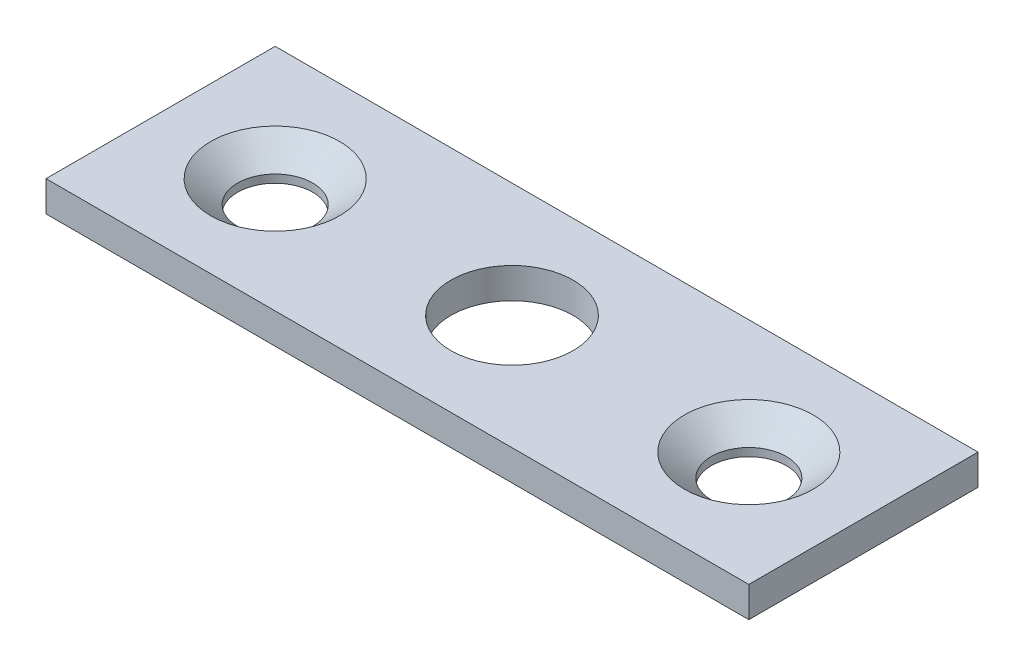
SolidWorks part; units mm, degrees
ref_plane "Front Plane" through (0, 0, 0) normal (0, 0, 1) x (1, 0, 0)
ref_plane "Top Plane" through (0, 0, 0) normal (0, 1, 0) x (1, 0, 0)
ref_plane "Right Plane" through (0, 0, 0) normal (1, 0, 0) x (0, 0, -1)
sketch "Sketch1" plane through (0, 0, 0) normal (0, 1, 0) x (1, 0, 0)
  line L1 (-23, -7.5) -> (23, -7.5)
  line L2 (-23, -7.5) -> (-23, 7.5)
  line L3 (-23, 7.5) -> (23, 7.5)
  line L4 (23, -7.5) -> (23, 7.5)
  line L5 (-23, -7.5) -> (23, 7.5) construction
  line L6 (-23, 7.5) -> (23, -7.5) construction
  circle A0 centre (0, 0) radius 4
  point P0 (0, 0)
  dimension "D2" = 8
  dimension "D1" = 46
  dimension "15" = 15
extrude "Boss-Extrude1" add sketch "Sketch1" along normal blind 2
hole_wizard "CSK for #8 Flat Head Machine Screw (100)1" positions "Sketch4" profile "Sketch5" countersink size "#8" standard "ANSI Inch"
sketch "Sketch4" plane through (0, 2, 0) normal (0, 1, 0) x (1, 0, 0)
  line L0 (0, 0) -> (0, 9.8013) construction
  point P0 (-15.5, 0)
  point P2 (15.5, 0)
  dimension "D1" = 31
sketch "Sketch5" plane through (-15.5, 2, 0) normal (1, 0, 0) x (0, 0, 1)
  line L0 (0, 0) -> (0, 26.4766)
  line L1 (0, 26.4766) -> (2.4574, 25)
  line L2 (2.4574, 25) -> (2.4574, 1.4759)
  line L3 (2.4574, 1.4759) -> (4.2164, 0)
  line L5 (4.2164, 0) -> (0, 0)
  line L6 (-2.4574, 1.4759) -> (-4.2164, 0) construction
  line L10 (0, 26.4766) -> (-2.4575, 25) construction
  line L11 (0, -6.35) -> (0, 107.95) construction
  dimension "Hole Dia." = 4.9149
  dimension "Hole Depth" = 25
  dimension "Near C'Sink Dia." = 8.4328
  dimension "Near C'Sink Angle" = 100
  dimension "Drill Angle" = 118
